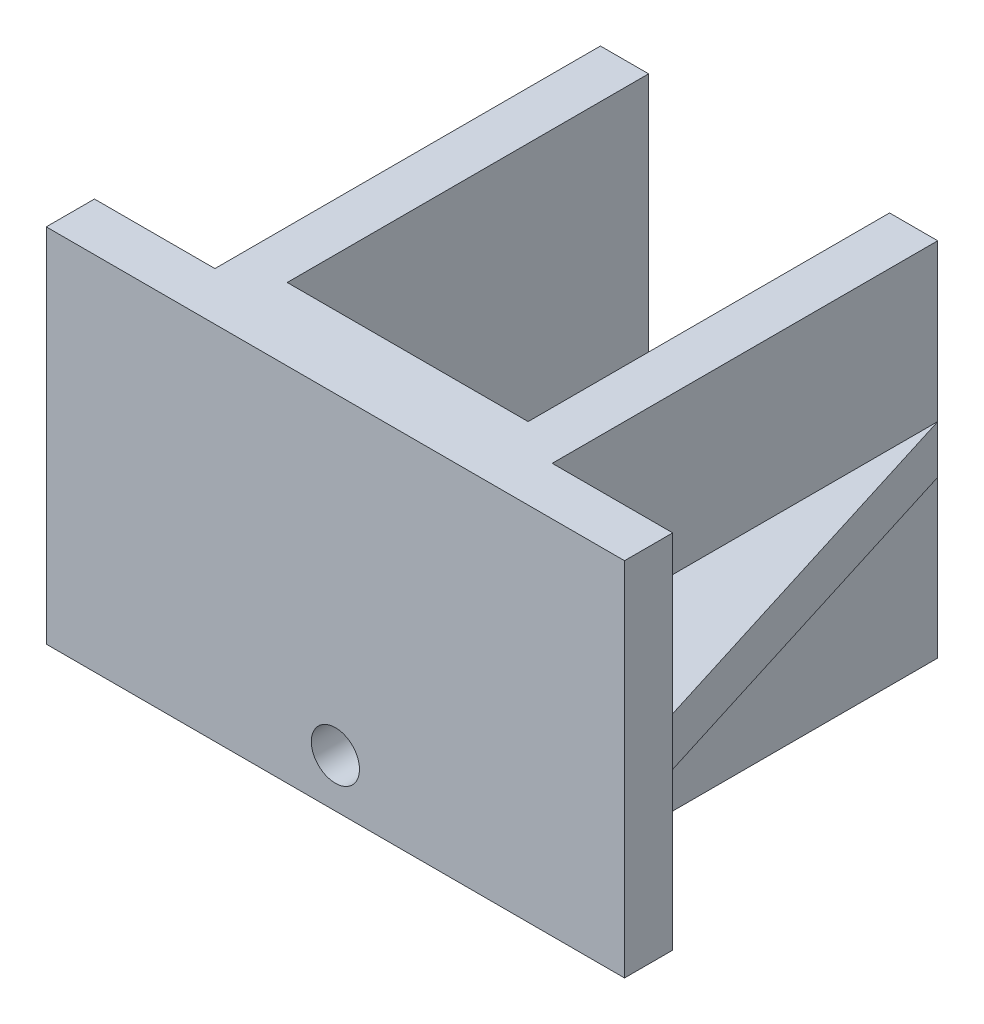
SolidWorks part; units mm, degrees
material "ABS"
ref_plane "Front Plane" through (0, 0, 0) normal (0, 0, 1) x (1, 0, 0)
ref_plane "Top Plane" through (0, 0, 0) normal (0, 1, 0) x (1, 0, 0)
ref_plane "Right Plane" through (0, 0, 0) normal (1, 0, 0) x (0, 0, -1)
sketch "Sketch1" plane through (0, 0, 0) normal (0, 1, 0) x (1, 0, 0)
  line L0 (0, 0) -> (0, -6) construction
  line L1 (10, 0) -> (-10, 0)
  line L2 (-10, 0) -> (-10, 30)
  line L3 (-10, 30) -> (-14, 30)
  line L4 (-24, -6) -> (-24, -2)
  line L5 (-24, -6) -> (24, -6)
  line L7 (-14, -2) -> (-14, 30)
  line L8 (-24, -2) -> (-14, -2)
  line L9 (24, -2) -> (14, -2)
  line L10 (14, -2) -> (14, 30)
  line L12 (24, -6) -> (24, -2)
  line L13 (10, 30) -> (14, 30)
  line L14 (10, 0) -> (10, 30)
  dimension "D1" = 10
  dimension "D2" = 30
  dimension "D3" = 6
  dimension "D4" = 4
  dimension "D5" = 10
  dimension "D6" = 4
extrude "Boss-Extrude1" add sketch "Sketch1" along normal mid plane 30
sketch "Sketch2" plane through (0, 0, 0) normal (0, 1, 0) x (1, 0, 0)
  line L0 (14, 30) -> (14, -2)
  line L1 (14, -2) -> (24, -2)
  line L2 (24, -2) -> (14, 30)
  point P3 (14.4577, 29.6016)
  point P4 (14.0578, 27.2123)
  point P6 (0, 0)
  point P8 (0, 0)
extrude "Boss-Extrude2" add sketch "Sketch2" along normal mid plane 4
mirror "Mirror1" about plane through (0, 0, 0) normal (1, 0, 0) of "Boss-Extrude2"
sketch "Sketch3" plane through (0, 0, 0) normal (0, 0, -1) x (-1, 0, 0)
  line L0 (0, 0) -> (0, -11) construction
  line L1 (0, -11) -> (0, -15) construction
  line L2 (-10, -15) -> (10, -15) construction
  circle A0 centre (0, -11) radius 2
  dimension "D1" = 4
extrude "Cut-Extrude1" cut sketch "Sketch3" against normal through all
